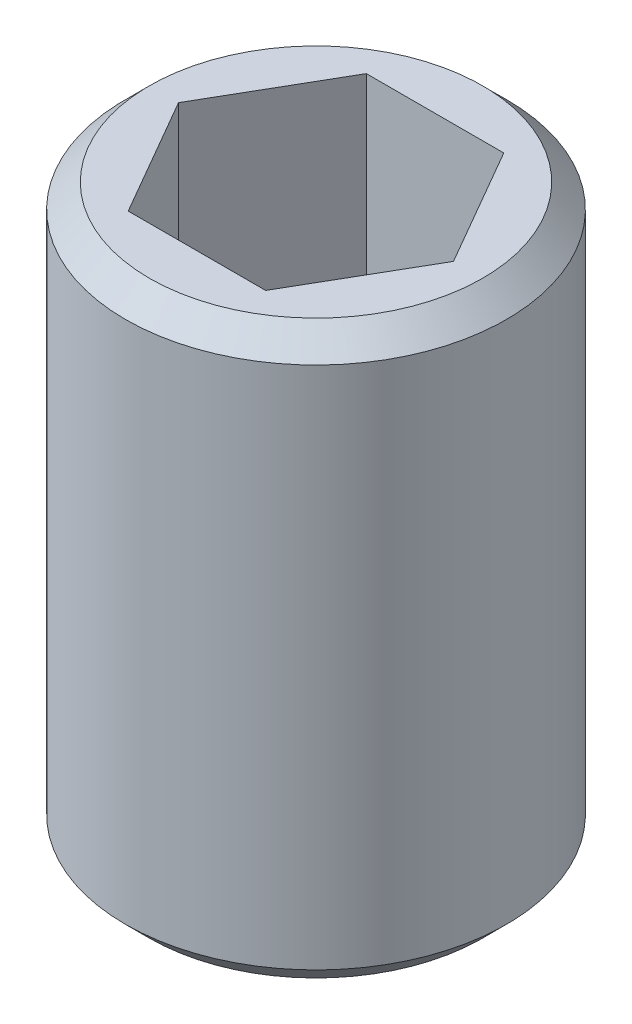
SolidWorks part; units mm, degrees
material "Plain Carbon Steel"
ref_plane "Front Plane" through (0, 0, 0) normal (0, 0, 1) x (1, 0, 0)
ref_plane "Top Plane" through (0, 0, 0) normal (0, 1, 0) x (1, 0, 0)
ref_plane "Right Plane" through (0, 0, 0) normal (1, 0, 0) x (0, 0, -1)
sketch "Sketch1" plane through (0, 0, 0) normal (0, 1, 0) x (1, 0, 0)
  circle A0 centre (0, 0) radius 4
  dimension "D1" = 8
extrude "Boss-Extrude1" add sketch "Sketch1" against normal blind 12
sketch "Sketch2" plane through (0, 0, 0) normal (0, 1, 0) x (1, 0, 0)
  circle A0 centre (0, 0) radius 2.1
  dimension "D1" = 4.2
extrude "Cut-Extrude1" cut sketch "Sketch2" against normal through all
cosmetic thread "Cosmetic Thread1" parameters "D2"=5
sketch "Sketch3" plane through (0, 0, 0) normal (0, 1, 0) x (1, 0, 0)
  line L1 (2.8868, 0) -> (1.4434, 2.5)
  line L2 (1.4434, 2.5) -> (-1.4434, 2.5)
  line L3 (-1.4434, 2.5) -> (-2.8868, 0)
  line L4 (-2.8868, 0) -> (-1.4434, -2.5)
  line L5 (-1.4434, -2.5) -> (1.4434, -2.5)
  line L6 (1.4434, -2.5) -> (2.8868, 0)
  circle A0 centre (0, 0) radius 2.5 construction
  dimension "D1" = 5
extrude "Cut-Extrude2" cut sketch "Sketch3" against normal blind 4
chamfer "Chamfer1" distance 0.5 angle 45 2 edges at (0, 0, 4) (0, -12, 4)
